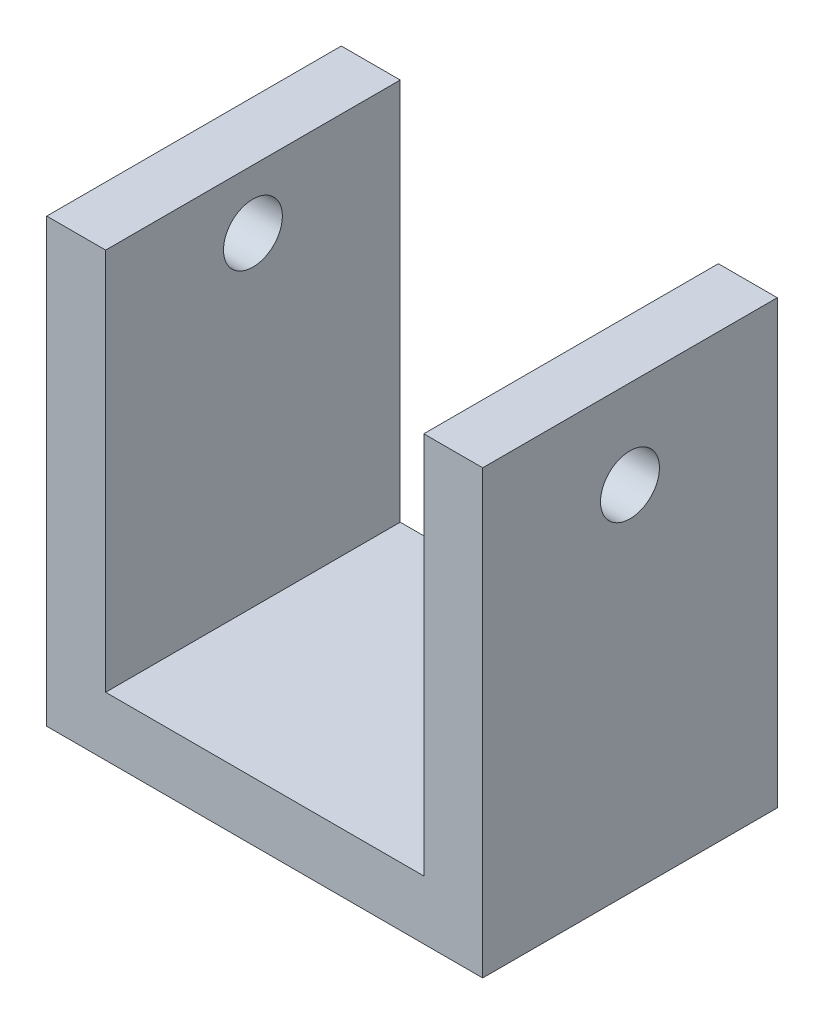
SolidWorks part; units mm, degrees
ref_plane "Front Plane" through (0, 0, 0) normal (0, 0, 1) x (1, 0, 0)
ref_plane "Top Plane" through (0, 0, 0) normal (0, 1, 0) x (1, 0, 0)
ref_plane "Right Plane" through (0, 0, 0) normal (1, 0, 0) x (0, 0, -1)
sketch "Sketch1" plane through (0, 0, 0) normal (0, 1, 0) x (1, 0, 0)
  line L1 (37, -25) -> (-37, -25)
  line L2 (37, -25) -> (37, 25)
  line L3 (37, 25) -> (-37, 25)
  line L4 (-37, -25) -> (-37, 25)
  line L5 (37, -25) -> (-37, 25) construction
  line L6 (37, 25) -> (-37, -25) construction
  point P0 (0, 0)
  dimension "D1" = 74
  dimension "D2" = 50
extrude "Boss-Extrude1" add sketch "Sketch1" along normal blind 10
sketch "Sketch2" plane through (0, 10, 0) normal (0, 1, 0) x (1, 0, 0)
  line L0 (-37, -25) -> (37, -25) construction
  line L1 (-37, 25) -> (-27, 25)
  line L2 (-37, 25) -> (-37, -25)
  line L3 (-37, -25) -> (-27, -25)
  line L4 (-27, 25) -> (-27, -25)
  line L5 (37, 25) -> (-37, 25) construction
  line L6 (37, 25) -> (27, 25)
  line L7 (37, 25) -> (37, -25)
  line L8 (37, -25) -> (27, -25)
  line L9 (27, 25) -> (27, -25)
  line L10 (37, -25) -> (37, 25) construction
  dimension "D1" = 10
  dimension "D2" = 10
extrude "Boss-Extrude2" add sketch "Sketch2" along normal blind 65
sketch "Sketch3" plane through (-27, 0, 0) normal (1, 0, 0) x (0, 0, -1)
  line L0 (-25, 75) -> (25, 75) construction
  circle A0 centre (0, 65) radius 5
  point P2 (0, 75)
  dimension "D1" = 10
  dimension "D2" = 10
extrude "Cut-Extrude1" cut sketch "Sketch3" against normal blind 60
sketch "Sketch4" plane through (27, 0, 0) normal (-1, 0, 0) x (0, 0, 1)
  line L0 (-25, 75) -> (25, 75) construction
  circle A0 centre (0, 60) radius 5
  point P2 (0, 75)
  dimension "D1" = 10
  dimension "D2" = 15
extrude "Cut-Extrude3" cut sketch "Sketch4" against normal blind 60
